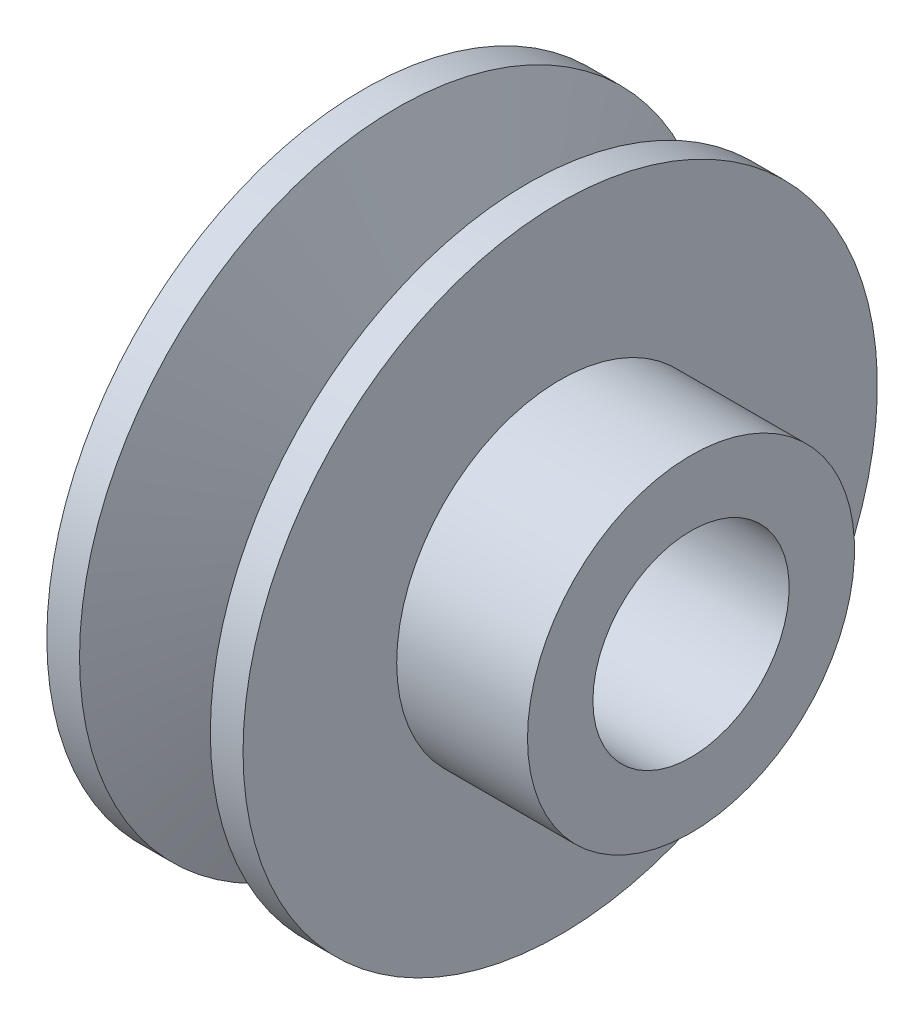
SolidWorks part; units mm, degrees
ref_plane "Front Plane" through (0, 0, 0) normal (0, 0, 1) x (1, 0, 0)
ref_plane "Top Plane" through (0, 0, 0) normal (0, 1, 0) x (1, 0, 0)
ref_plane "Right Plane" through (0, 0, 0) normal (1, 0, 0) x (0, 0, -1)
sketch "Sketch1" plane through (0, 0, 0) normal (0, 1, 0) x (1, 0, 0)
  line L0 (0, 0) -> (100.5231, 0) construction
  line L1 (0, 0) -> (0, 48.4923)
  line L2 (0, 48.4923) -> (5, 48.4923)
  line L3 (5, 48.4923) -> (13.5505, 25)
  line L4 (13.5505, 25) -> (16.4495, 25)
  line L5 (16.4495, 25) -> (25, 48.4923)
  line L6 (25, 48.4923) -> (30, 48.4923)
  line L7 (30, 48.4923) -> (30, 25)
  line L8 (30, 25) -> (38.2429, 25)
  line L11 (39.2429, 25) -> (39.25, 25)
  line L13 (40.7429, 19.25) -> (40.75, 19.25)
  line L16 (40.7429, 25) -> (40.75, 25)
  line L17 (50, 25) -> (50, 15)
  line L18 (50, 15) -> (5, 15)
  line L19 (5, 15) -> (5, 0)
  line L20 (40, 71.5917) -> (40, -13.6395) construction
  line L21 (0, 0) -> (5, 0)
  line L22 (39.2429, 15) -> (40.7429, 15)
  line L23 (38.2429, 15) -> (38.2429, 25)
  line L24 (41.7429, 25) -> (50, 25)
  line L25 (41.7429, 25) -> (41.7429, 15)
  line L26 (38.2429, 25) -> (41.7429, 25)
  circle A1 centre (40, 20.5118) radius 1.5
  dimension "D1" = 25
  dimension "D2" = 10
  dimension "D3" = 40
  dimension "D4" = 5
  dimension "D5" = 20
  dimension "D6" = 5
  dimension "D7" = 5
  dimension "D8" = 20
  dimension "D12" = 10
  dimension "D14" = 25
  dimension "D15" = 25
revolve "Revolve10" add sketch "Sketch1" angle 360 about L0
